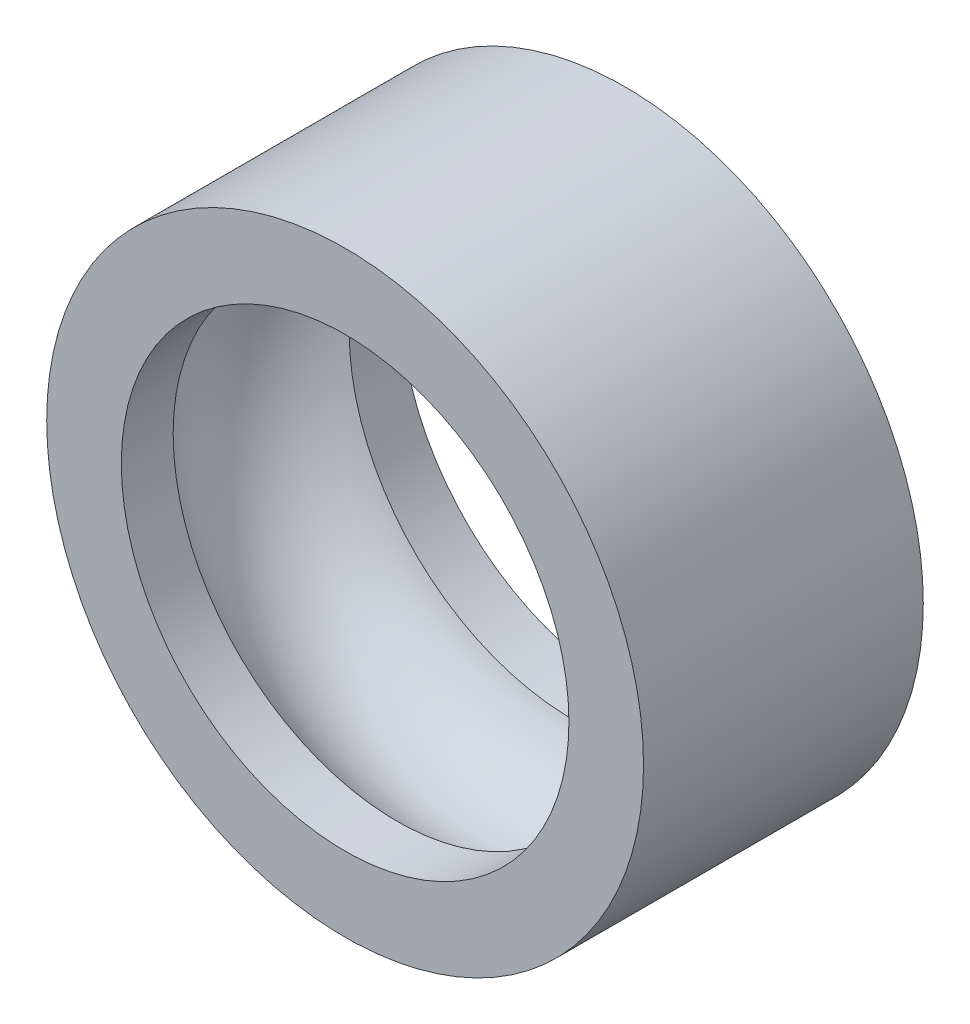
SolidWorks part; units mm, degrees
ref_plane "Front Plane" through (0, 0, 0) normal (0, 0, 1) x (1, 0, 0)
ref_plane "Top Plane" through (0, 0, 0) normal (0, 1, 0) x (1, 0, 0)
ref_plane "Right Plane" through (0, 0, 0) normal (1, 0, 0) x (0, 0, -1)
sketch "Sketch2" plane through (0, 0, 0) normal (0, 0, 1) x (1, 0, 0)
  circle A0 centre (0, 0) radius 3.2
  circle A1 centre (0, 0) radius 2.4
  dimension "D1" = 6.4
  dimension "D2" = 4.8
extrude "Boss-Extrude1" add sketch "Sketch2" along normal blind 3
sketch "Sketch3" plane through (0, 0, 0) normal (1, 0, 0) x (0, 0, -1)
  line L0 (0, 2.4) -> (-3, 2.4) construction
  line L1 (-1.5, 2.07) -> (-1.5, 3.2) construction
  line L2 (0, 3.2) -> (-3, 3.2) construction
  line L3 (0, 0) -> (-9.4795, 0) construction
  line L4 (1.65, 0) -> (-1.65, 0) construction
  circle A0 centre (-1.5, 2.07) radius 1
  dimension "D1" = 2
  dimension "D2" = 0.33
revolve "Cut-Revolve1" cut sketch "Sketch3" angle 360 about L3
equation "\"bScale\"= 8"
equation "\"D1@Sketch2\"=\"bScale\" * 0.8"
equation "\"D2@Sketch2\"=\"bScale\"*0.6"
